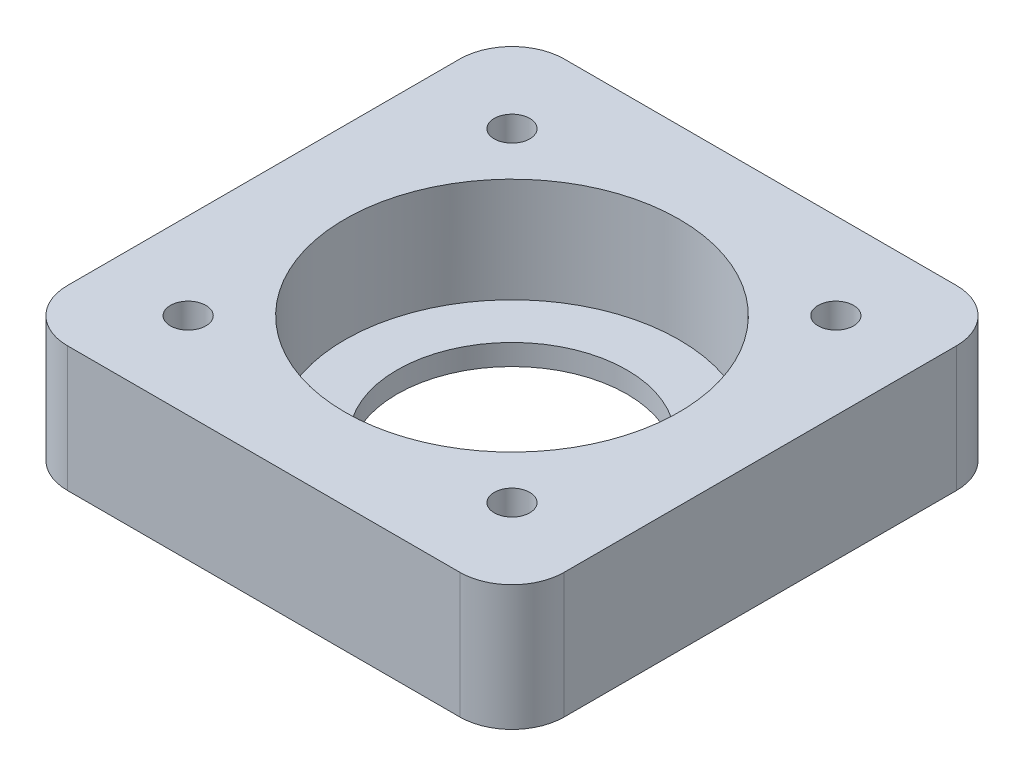
SolidWorks part; units mm, degrees
ref_plane "Front Plane" through (0, 0, 0) normal (0, 0, 1) x (1, 0, 0)
ref_plane "Top Plane" through (0, 0, 0) normal (0, 1, 0) x (1, 0, 0)
ref_plane "Right Plane" through (0, 0, 0) normal (1, 0, 0) x (0, 0, -1)
sketch "Sketch1" plane through (0, 0, 0) normal (0, 1, 0) x (1, 0, 0)
  line L1 (-23.775, 23.775) -> (23.775, 23.775)
  line L2 (-23.775, 23.775) -> (-23.775, -23.775)
  line L3 (-23.775, -23.775) -> (23.775, -23.775)
  line L4 (23.775, 23.775) -> (23.775, -23.775)
  line L5 (-23.775, 23.775) -> (23.775, -23.775) construction
  line L6 (-23.775, -23.775) -> (23.775, 23.775) construction
  line L7 (-15.5, 15.5) -> (15.5, 15.5)
  line L8 (-15.5, 15.5) -> (-15.5, -15.5)
  line L9 (-15.5, -15.5) -> (15.5, -15.5)
  line L10 (15.5, 15.5) -> (15.5, -15.5)
  line L11 (-15.5, 15.5) -> (15.5, -15.5) construction
  line L12 (-15.5, -15.5) -> (15.5, 15.5) construction
  circle A0 centre (-15.5, 15.5) radius 1.7
  circle A1 centre (15.5, 15.5) radius 1.7
  circle A2 centre (15.5, -15.5) radius 1.7
  circle A3 centre (-15.5, -15.5) radius 1.7
  circle A4 centre (0, 0) radius 16
  point P0 (0, 0)
  point P6 (0, 0)
  dimension "D3" = 3.4
  dimension "D4" = 32
  dimension "D1" = 47.55
  dimension "D2" = 31
extrude "Boss-Extrude1" add sketch "Sketch1" along normal blind 12 contours L4 L1 L2 L3 A4 L10 A2 L9 A3 L8 A0 L7 A1 | A4 L7 A0 L8 | A4 L10 A1 L7 | A4 L9 A2 L10 | A4 L8 A3 L9
sketch "Sketch2" plane through (0, 0, 0) normal (0, -1, 0) x (1, 0, 0)
  circle A0 centre (0, 0) radius 16
  circle A1 centre (0, 0) radius 11
  circle M3 centre (0, 0) radius 16
  dimension "D1" = 5
extrude "Boss-Extrude2" add sketch "Sketch2" against normal blind 2 contours A1 M3 | A0
fillet "Fillet1" radius 5 4 edges at (23.775, 6, -23.775) (23.775, 6, 23.775) (-23.775, 6, 23.775) (-23.775, 6, -23.775)
